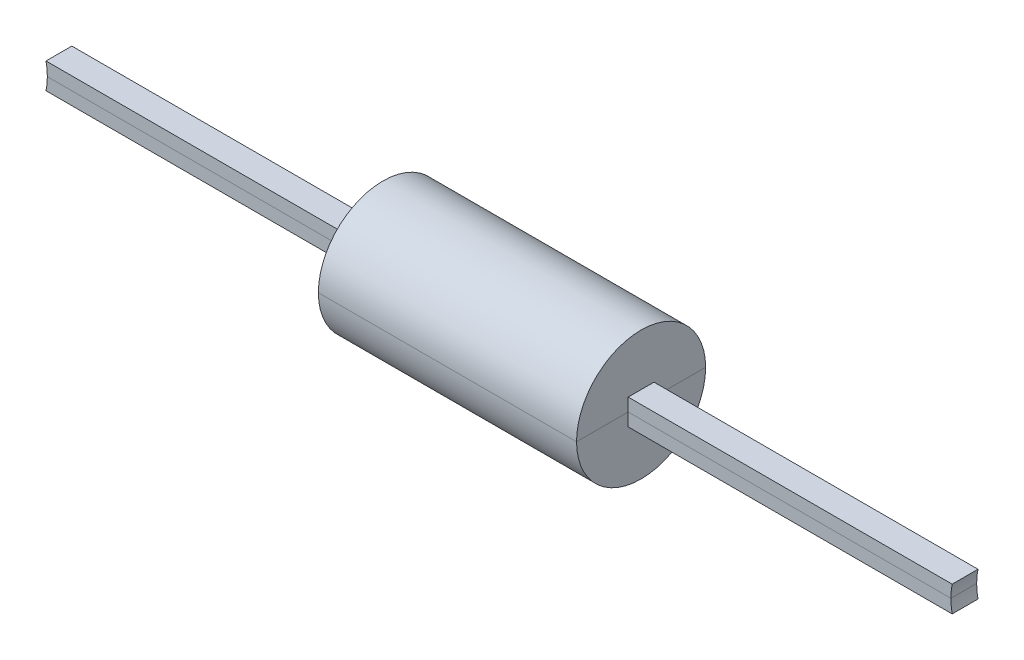
SolidWorks part; units mm, degrees
ref_plane "Front Plane" through (0, 0, 0) normal (0, 0, 1) x (1, 0, 0)
ref_plane "Top Plane" through (0, 0, 0) normal (0, 1, 0) x (1, 0, 0)
ref_plane "Right Plane" through (0, 0, 0) normal (1, 0, 0) x (0, 0, -1)
sketch "Sketch1" plane through (0, 0, 0) normal (1, 0, 0) x (0, 0, -1)
  circle A0 centre (0, 0) radius 5
  dimension "D1" = 10
extrude "Boss-Extrude1" add sketch "Sketch1" along normal mid plane 20
sketch "Sketch5" plane through (0, 0, 0) normal (0, 0, 1) x (1, 0, 0)
  line L1 (-40, 1) -> (40, 1)
  line L2 (-40, 1) -> (-40, -1)
  line L3 (-40, -1) -> (40, -1)
  line L4 (40, 1) -> (40, -1)
  line L5 (-40, 1) -> (40, -1) construction
  line L6 (-40, -1) -> (40, 1) construction
  circle A0 centre (-40, 0) radius 5
  circle A1 centre (40, 0) radius 5
  point P0 (0, 0)
  dimension "D3" = 10
  dimension "D1" = 80
  dimension "D2" = 2
extrude "Boss-Extrude5" add sketch "Sketch5" along normal mid plane 2 contours A1 L1 A0 L3
split "Split1" trim tools "Top Plane" bodies to split 106 resulting bodies 107 108
